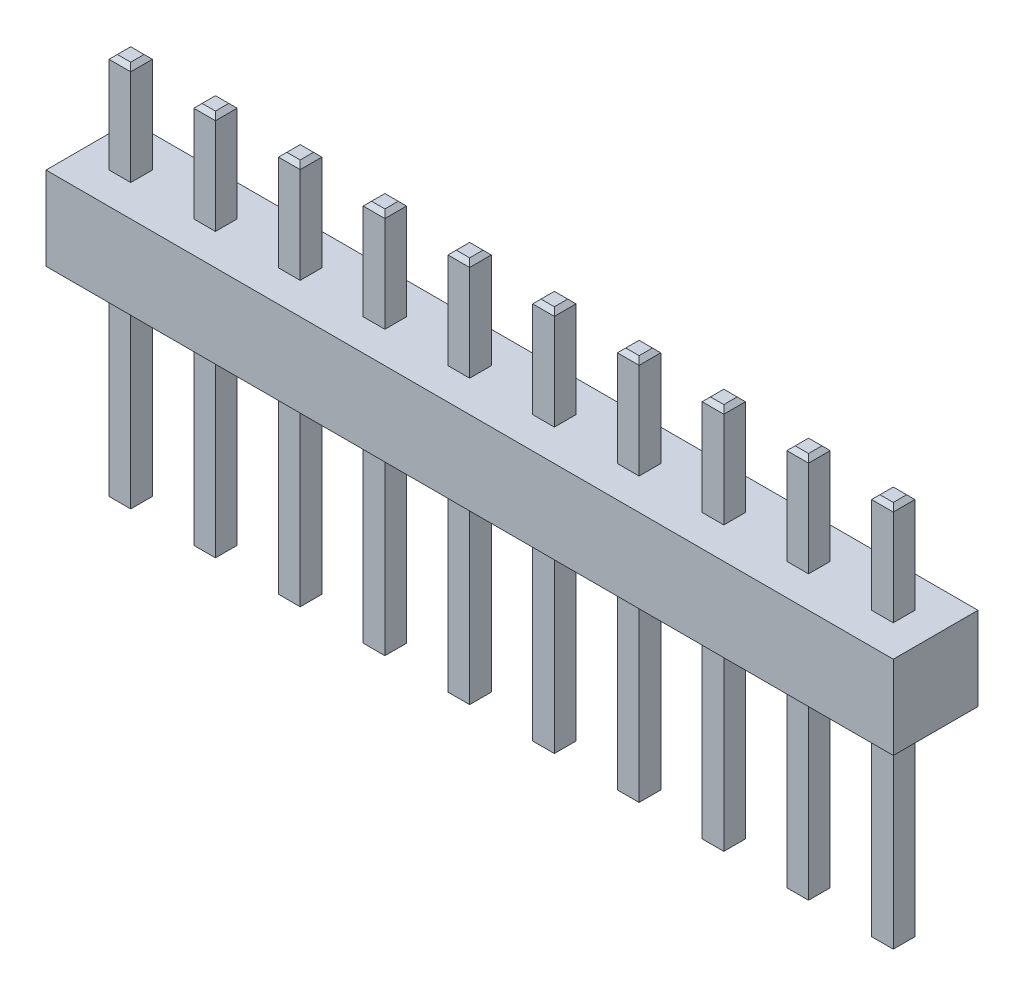
SolidWorks part; units mm, degrees
ref_plane "Front Plane" through (0, 0, 0) normal (0, 0, 1) x (1, 0, 0)
ref_plane "Top Plane" through (0, 0, 0) normal (0, 1, 0) x (1, 0, 0)
ref_plane "Right Plane" through (0, 0, 0) normal (1, 0, 0) x (0, 0, -1)
sketch "Sketch3" plane through (0, 0, 0) normal (0, 1, 0) x (1, 0, 0)
  line L1 (-12.7, -1.27) -> (12.7, -1.27)
  line L2 (-12.7, -1.27) -> (-12.7, 1.27)
  line L3 (-12.7, 1.27) -> (12.7, 1.27)
  line L4 (12.7, -1.27) -> (12.7, 1.27)
  line L5 (-12.7, -1.27) -> (12.7, 1.27) construction
  line L6 (-12.7, 1.27) -> (12.7, -1.27) construction
  point P0 (0, 0)
  dimension "D1" = 2.54
  dimension "D2" = 25.4
extrude "Boss-Extrude1" add sketch "Sketch3" along normal blind 2.5
sketch "Sketch4" plane through (0, 2.5, 0) normal (0, 1, 0) x (1, 0, 0)
  line L0 (0, 0) -> (-12.7, 0) construction
  line L1 (0, 0) -> (12.7, 0) construction
  line L2 (0, 0) -> (0, 1.27) construction
  line L3 (12.7, 1.27) -> (-12.7, 1.27) construction
  line L4 (12.7, -1.27) -> (12.7, 1.27) construction
  line L5 (0.945, 0.325) -> (1.595, 0.325)
  line L6 (1.595, -0.325) -> (1.595, 0.325)
  line L7 (0.945, -0.325) -> (1.595, -0.325)
  line L8 (-12.7, 1.27) -> (-12.7, -1.27) construction
  line L9 (0.945, -0.325) -> (0.945, 0.325)
  line L10 (3.485, 0.325) -> (4.135, 0.325)
  line L11 (4.135, -0.325) -> (4.135, 0.325)
  line L12 (3.485, -0.325) -> (4.135, -0.325)
  line L13 (3.485, -0.325) -> (3.485, 0.325)
  line L14 (6.025, 0.325) -> (6.675, 0.325)
  line L15 (6.675, -0.325) -> (6.675, 0.325)
  line L16 (6.025, -0.325) -> (6.675, -0.325)
  line L17 (6.025, -0.325) -> (6.025, 0.325)
  line L18 (8.565, 0.325) -> (9.215, 0.325)
  line L19 (9.215, -0.325) -> (9.215, 0.325)
  line L20 (8.565, -0.325) -> (9.215, -0.325)
  line L21 (8.565, -0.325) -> (8.565, 0.325)
  line L22 (11.105, 0.325) -> (11.755, 0.325)
  line L23 (11.755, -0.325) -> (11.755, 0.325)
  line L24 (11.105, -0.325) -> (11.755, -0.325)
  line L25 (11.105, -0.325) -> (11.105, 0.325)
  line L26 (-4.135, 0.325) -> (-3.485, 0.325)
  line L27 (-3.485, -0.325) -> (-3.485, 0.325)
  line L28 (-4.135, -0.325) -> (-3.485, -0.325)
  line L29 (-4.135, -0.325) -> (-4.135, 0.325)
  line L30 (-6.675, 0.325) -> (-6.025, 0.325)
  line L31 (-1.595, -0.325) -> (-0.945, -0.325)
  line L32 (-1.595, -0.325) -> (-1.595, 0.325)
  line L33 (-1.595, 0.325) -> (-0.945, 0.325)
  line L34 (-0.945, -0.325) -> (-0.945, 0.325)
  line L35 (-1.595, -0.325) -> (-0.945, 0.325) construction
  line L36 (-1.595, 0.325) -> (-0.945, -0.325) construction
  line L37 (-6.025, -0.325) -> (-6.025, 0.325)
  line L38 (-6.675, -0.325) -> (-6.025, -0.325)
  line L39 (-6.675, -0.325) -> (-6.675, 0.325)
  line L40 (-9.215, 0.325) -> (-8.565, 0.325)
  line L41 (-8.565, -0.325) -> (-8.565, 0.325)
  line L42 (-9.215, -0.325) -> (-8.565, -0.325)
  line L43 (-9.215, -0.325) -> (-9.215, 0.325)
  line L44 (-11.755, 0.325) -> (-11.105, 0.325)
  line L45 (-11.105, -0.325) -> (-11.105, 0.325)
  line L46 (-11.755, -0.325) -> (-11.105, -0.325)
  line L47 (-11.755, -0.325) -> (-11.755, 0.325)
  point P13 (-3.81, 1.27)
  point P18 (-1.27, 0)
  dimension "D1" = 1.27
  dimension "D2" = 6
  dimension "D3" = 5
  dimension "D5" = 0.65
  dimension "D6" = 0.65
extrude "Boss-Extrude2" add sketch "Sketch4" along normal blind 3
sketch "Sketch5" plane through (0, 0, 0) normal (0, -1, 0) x (1, 0, 0)
  line L0 (0, 0) -> (-12.7, 0) construction
  line L1 (0.945, 0.325) -> (1.595, 0.325)
  line L2 (0, 0) -> (0, 1.27) construction
  line L3 (-12.7, 1.27) -> (12.7, 1.27) construction
  line L4 (0.945, -0.325) -> (0.945, 0.325)
  line L5 (2.4834, 6.6353) -> (2.367, 6.5964) construction
  line L6 (1.595, -0.325) -> (1.595, 0.325)
  line L7 (0.945, -0.325) -> (1.595, -0.325)
  line L8 (3.485, 0.325) -> (4.135, 0.325)
  line L9 (-12.7, -1.27) -> (-12.7, 1.27) construction
  line L10 (3.485, -0.325) -> (3.485, 0.325)
  line L11 (4.135, -0.325) -> (4.135, 0.325)
  line L12 (3.485, -0.325) -> (4.135, -0.325)
  line L13 (6.025, 0.325) -> (6.675, 0.325)
  line L14 (6.025, -0.325) -> (6.025, 0.325)
  line L15 (6.675, -0.325) -> (6.675, 0.325)
  line L16 (6.025, -0.325) -> (6.675, -0.325)
  line L17 (8.565, 0.325) -> (9.215, 0.325)
  line L18 (8.565, -0.325) -> (8.565, 0.325)
  line L19 (9.215, -0.325) -> (9.215, 0.325)
  line L20 (8.565, -0.325) -> (9.215, -0.325)
  line L21 (11.105, 0.325) -> (11.755, 0.325)
  line L22 (11.105, -0.325) -> (11.105, 0.325)
  line L23 (11.755, -0.325) -> (11.755, 0.325)
  line L24 (11.105, -0.325) -> (11.755, -0.325)
  line L25 (-4.135, 0.325) -> (-3.485, 0.325)
  line L26 (-4.135, -0.325) -> (-4.135, 0.325)
  line L27 (-3.485, -0.325) -> (-3.485, 0.325)
  line L28 (-4.135, -0.325) -> (-3.485, -0.325)
  line L29 (-6.675, 0.325) -> (-6.025, 0.325)
  line L30 (-6.675, -0.325) -> (-6.675, 0.325)
  line L31 (-6.025, -0.325) -> (-6.025, 0.325)
  line L32 (-1.595, -0.325) -> (-0.945, -0.325)
  line L33 (-1.595, -0.325) -> (-1.595, 0.325)
  line L34 (-1.595, 0.325) -> (-0.945, 0.325)
  line L35 (-0.945, -0.325) -> (-0.945, 0.325)
  line L36 (-1.595, -0.325) -> (-0.945, 0.325) construction
  line L37 (-1.595, 0.325) -> (-0.945, -0.325) construction
  line L38 (-6.675, -0.325) -> (-6.025, -0.325)
  line L39 (-9.215, 0.325) -> (-8.565, 0.325)
  line L40 (-9.215, -0.325) -> (-9.215, 0.325)
  line L41 (-8.565, -0.325) -> (-8.565, 0.325)
  line L42 (-9.215, -0.325) -> (-8.565, -0.325)
  line L43 (-11.755, 0.325) -> (-11.105, 0.325)
  line L44 (-11.755, -0.325) -> (-11.755, 0.325)
  line L45 (-11.105, -0.325) -> (-11.105, 0.325)
  line L46 (-11.755, -0.325) -> (-11.105, -0.325)
  point P15 (-1.27, 1.27)
  point P20 (-1.27, 0)
  dimension "D1" = 0.65
  dimension "D2" = 0.65
  dimension "D3" = 1.27
  dimension "D4" = 6
  dimension "D5" = 5
extrude "Boss-Extrude3" add sketch "Sketch5" along normal blind 6.1
chamfer "Chamfer1" distance 0.125 angle 45 80 edges at (-11.43, -6.1, -0.325) (-11.755, -6.1, 0) (-11.43, -6.1, 0.325) (-11.105, -6.1, 0) (-8.89, -6.1, -0.325) (-9.215, -6.1, 0) (-8.89, -6.1, 0.325) (-8.565, -6.1, 0) (-6.35, -6.1, -0.325) (-6.675, -6.1, 0) (-6.35, -6.1, 0.325) (-6.025, -6.1, 0) (-3.81, -6.1, -0.325) (-4.135, -6.1, 0) (-3.81, -6.1, 0.325) (-3.485, -6.1, 0) (-1.27, -6.1, -0.325) (-1.595, -6.1, 0) (-1.27, -6.1, 0.325) (-0.945, -6.1, 0) (1.27, -6.1, -0.325) (0.945, -6.1, 0) (1.27, -6.1, 0.325) (1.595, -6.1, 0) (3.81, -6.1, -0.325) (3.485, -6.1, 0) (3.81, -6.1, 0.325) (4.135, -6.1, 0) (6.35, -6.1, -0.325) (6.025, -6.1, 0) (6.35, -6.1, 0.325) (6.675, -6.1, 0) (8.89, -6.1, -0.325) (8.565, -6.1, 0) (8.89, -6.1, 0.325) (9.215, -6.1, 0) (11.43, -6.1, -0.325) (11.105, -6.1, 0) (11.43, -6.1, 0.325) (11.755, -6.1, 0) (11.43, 5.5, 0.325) (11.105, 5.5, 0) (11.43, 5.5, -0.325) (11.755, 5.5, 0) (8.89, 5.5, 0.325) (8.565, 5.5, 0) (8.89, 5.5, -0.325) (9.215, 5.5, 0) (6.35, 5.5, 0.325) (6.025, 5.5, 0) (6.35, 5.5, -0.325) (6.675, 5.5, 0) (3.81, 5.5, 0.325) (3.485, 5.5, 0) (3.81, 5.5, -0.325) (4.135, 5.5, 0) (1.27, 5.5, 0.325) (0.945, 5.5, 0) (1.27, 5.5, -0.325) (1.595, 5.5, 0) (-1.27, 5.5, 0.325) (-1.595, 5.5, 0) (-1.27, 5.5, -0.325) (-0.945, 5.5, 0) (-3.81, 5.5, 0.325) (-4.135, 5.5, 0) (-3.81, 5.5, -0.325) (-3.485, 5.5, 0) (-6.35, 5.5, 0.325) (-6.675, 5.5, 0) (-6.35, 5.5, -0.325) (-6.025, 5.5, 0) (-8.89, 5.5, 0.325) (-9.215, 5.5, 0) (-8.89, 5.5, -0.325) (-8.565, 5.5, 0) (-11.43, 5.5, 0.325) (-11.755, 5.5, 0) (-11.43, 5.5, -0.325) (-11.105, 5.5, 0)
sketch "Sketch6" plane through (0, 2.5, 0) normal (0, 1, 0) x (1, 0, 0)
  line L0 (-11.43, 0.325) -> (-11.43, -0.325) construction
  line L1 (-11.105, 0.325) -> (-11.755, 0.325) construction
  line L2 (-11.755, -0.325) -> (-11.105, -0.325) construction
  line L3 (11.43, 0.325) -> (11.43, -0.325) construction
  line L4 (11.105, 0.325) -> (11.755, 0.325) construction
  line L5 (11.755, -0.325) -> (11.105, -0.325) construction
  point P12 (11.43, 0)
  point P13 (-11.43, 0)
sketch "Sketch7" plane through (0, 0, 0) normal (0, -1, 0) x (1, 0, 0)
  line L0 (-11.43, 0.325) -> (-11.43, -0.325) construction
  line L1 (-11.755, 0.325) -> (-11.105, 0.325) construction
  line L2 (-11.755, -0.325) -> (-11.105, -0.325) construction
  line L3 (11.43, 0.325) -> (11.43, -0.325) construction
  line L4 (11.105, 0.325) -> (11.755, 0.325) construction
  line L5 (11.755, -0.325) -> (11.105, -0.325) construction
  point P12 (11.43, 0)
  point P13 (-11.43, 0)
